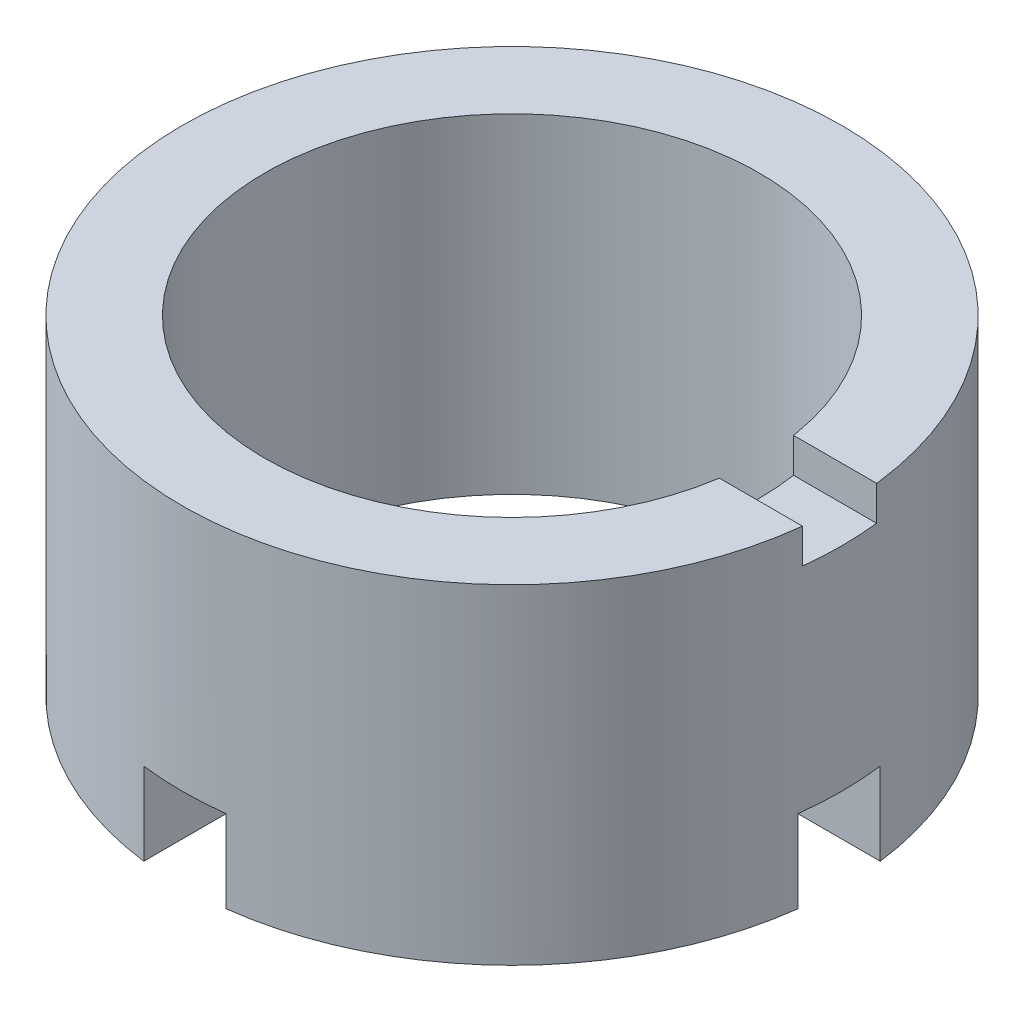
SolidWorks part; units mm, degrees
ref_plane "Front Plane" through (0, 0, 0) normal (0, 0, 1) x (1, 0, 0)
ref_plane "Top Plane" through (0, 0, 0) normal (0, 1, 0) x (1, 0, 0)
ref_plane "Right Plane" through (0, 0, 0) normal (1, 0, 0) x (0, 0, -1)
sketch "Sketch1" plane through (0, 0, 0) normal (0, 1, 0) x (1, 0, 0)
  circle A0 centre (0, 0) radius 25.4
  circle A1 centre (0, 0) radius 19.05
  dimension "D1" = 50.8
  dimension "D2" = 38.1
extrude "Boss-Extrude1" add sketch "Sketch1" along normal blind 25.4
sketch "Sketch2" plane through (0, 0, 0) normal (0, -1, 0) x (1, 0, 0)
  line L0 (0, 25.4) -> (0, -25.4) construction
  line L1 (25.4, 0) -> (-25.4, 0) construction
  line L2 (17.78, 3.175) -> (17.78, -3.175)
  line L3 (-3.175, 33.02) -> (3.175, 33.02)
  line L4 (-3.175, 33.02) -> (-3.175, 17.78)
  line L5 (-3.175, 17.78) -> (3.175, 17.78)
  line L6 (3.175, 33.02) -> (3.175, 17.78)
  line L7 (-3.175, 33.02) -> (3.175, 17.78) construction
  line L8 (-3.175, 17.78) -> (3.175, 33.02) construction
  line L9 (33.02, 3.175) -> (17.78, 3.175)
  line L10 (33.02, -3.175) -> (17.78, -3.175)
  line L11 (33.02, 3.175) -> (33.02, -3.175)
  line L12 (0, 0) -> (3.175, 17.78) construction
  line L13 (0, 0) -> (17.78, -3.175) construction
  circle A0 centre (0, 0) radius 25.4 construction
  point P11 (-3.175, 25.2008)
  point P12 (3.175, 25.2008)
  dimension "D1" = 6.35
  dimension "D2" = 15.24
  dimension "D4" = 90
  dimension "D3" = 2
extrude "Cut-Extrude1" cut sketch "Sketch2" against normal blind 6.35
sketch "Sketch3" plane through (0, 25.4, 0) normal (0, 1, 0) x (1, 0, 0)
  line L0 (0, 0) -> (25.4, 0) construction
  line L2 (15.4971, -2.8575) -> (35.3029, -2.8575)
  line L3 (15.4971, -2.8575) -> (15.4971, 2.8575)
  line L4 (15.4971, 2.8575) -> (35.3029, 2.8575)
  line L5 (35.3029, -2.8575) -> (35.3029, 2.8575)
  line L6 (15.4971, -2.8575) -> (35.3029, 2.8575) construction
  line L7 (15.4971, 2.8575) -> (35.3029, -2.8575) construction
  circle A0 centre (0, 0) radius 25.4 construction
  dimension "D1" = 5.715
extrude "Cut-Extrude2" cut sketch "Sketch3" against normal blind 2.667
